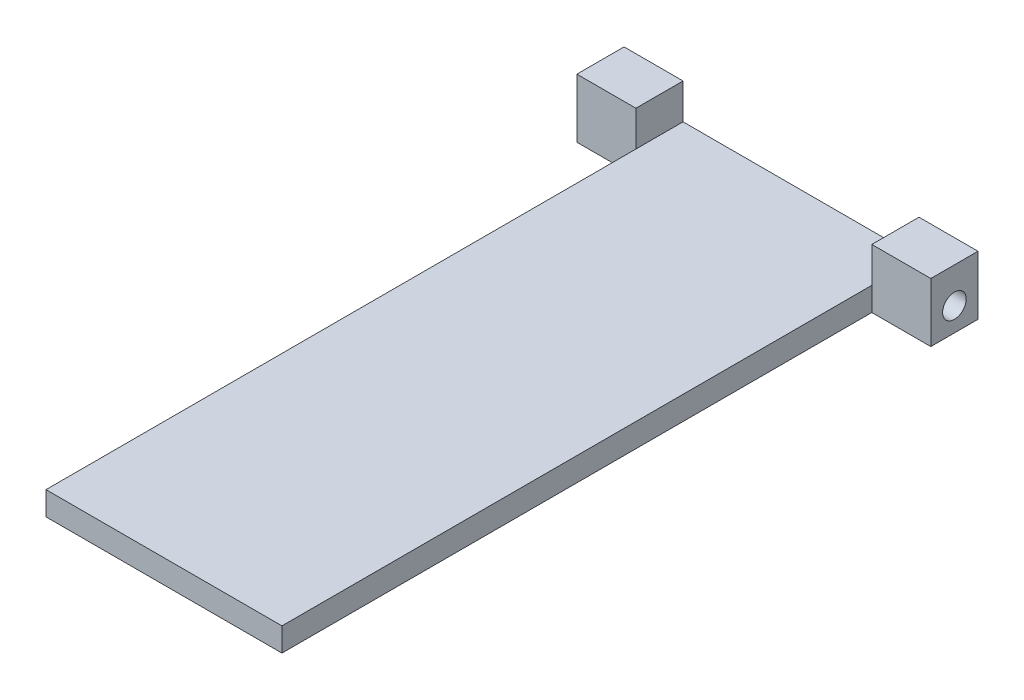
SolidWorks part; units mm, degrees
ref_plane "Front Plane" through (0, 0, 0) normal (0, 0, 1) x (1, 0, 0)
ref_plane "Top Plane" through (0, 0, 0) normal (0, 1, 0) x (1, 0, 0)
ref_plane "Right Plane" through (0, 0, 0) normal (1, 0, 0) x (0, 0, -1)
ref_plane "Plane2" through (0, -50, 0) normal (0, -1, 0) x (-1, 0, 0)
sketch "Sketch5" plane through (0, -50, 0) normal (0, -1, 0) x (-1, 0, 0)
  line L0 (50, 85) -> (-50, 85)
  line L1 (-50, 85) -> (-50, -85)
  line L2 (-50, -85) -> (50, -85)
  line L3 (50, -85) -> (50, 85)
extrude "Boss-Extrude2" add sketch "Sketch5" against normal blind 10 separate body
sketch "Sketch7" plane through (-50, 0, 0) normal (-1, 0, 0) x (0, 0, 1)
  line L0 (-85, -50) -> (-65, -50)
  line L1 (85, -50) -> (-85, -50) construction
  line L2 (-65, -50) -> (-65, -25)
  line L3 (-65, -25) -> (-85, -25)
  line L4 (-85, -25) -> (-85, -50)
  dimension "D1" = 20
  dimension "D2" = 25
extrude "Boss-Extrude3" add sketch "Sketch7" along normal blind 25
sketch "Sketch8" plane through (50, 0, 0) normal (1, 0, 0) x (0, 0, -1)
  line L0 (65, -50) -> (65, -25)
  line L1 (65, -25) -> (85, -25)
  line L2 (85, -25) -> (85, -50)
  line L3 (85, -50) -> (65, -50)
extrude "Boss-Extrude4" add sketch "Sketch8" along normal blind 25
sketch "Sketch11" plane through (-75, 0, 0) normal (-1, 0, 0) x (0, 0, 1)
  line L0 (-85, -25) -> (-85, -50) construction
  line L1 (-85, -50) -> (-65, -50) construction
  circle A0 centre (-75, -40) radius 5
  dimension "D3" = 10
  dimension "D1" = 10
  dimension "D2" = 10
extrude "Cut-Extrude1" cut sketch "Sketch11" against normal blind 20
sketch "Sketch12" plane through (75, 0, 0) normal (1, 0, 0) x (0, 0, -1)
  line L0 (65, -50) -> (85, -50) construction
  line L1 (85, -50) -> (85, -25) construction
  circle A0 centre (75, -40) radius 5
  dimension "D1" = 10
  dimension "D2" = 10
  dimension "D3" = 10
extrude "Cut-Extrude2" cut sketch "Sketch12" against normal blind 20
sketch "Sketch17" plane through (0, 0, 85) normal (0, 0, 1) x (1, 0, 0)
  line L0 (-50, -50) -> (-50, -40)
  line L1 (-50, -40) -> (50, -40)
  line L2 (50, -40) -> (50, -50)
  line L3 (50, -50) -> (-50, -50)
extrude "Boss-Extrude6" add sketch "Sketch17" along normal blind 100
